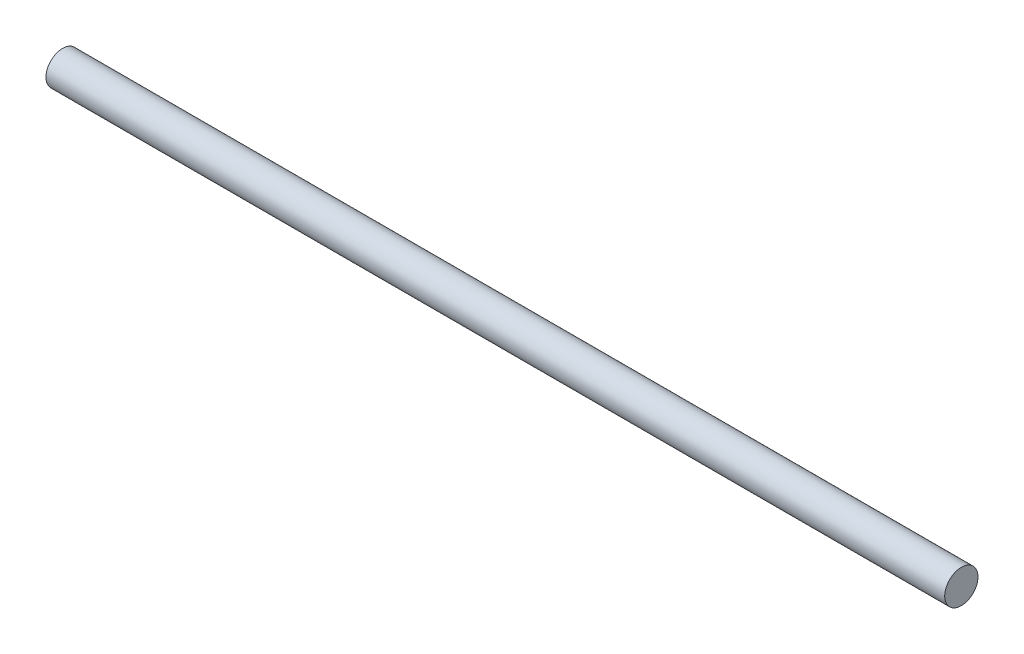
SolidWorks part; units mm, degrees
material "Plain Carbon Steel"
ref_plane "Front Plane" through (0, 0, 0) normal (0, 0, 1) x (1, 0, 0)
ref_plane "Top Plane" through (0, 0, 0) normal (0, 1, 0) x (1, 0, 0)
ref_plane "Right Plane" through (0, 0, 0) normal (1, 0, 0) x (0, 0, -1)
sketch "Sketch1" plane through (0, 0, 0) normal (1, 0, 0) x (0, 0, -1)
  circle A0 centre (0, 0) radius 2.5
  dimension "D1" = 5
extrude "Boss-Extrude1" add sketch "Sketch1" along normal blind 135
